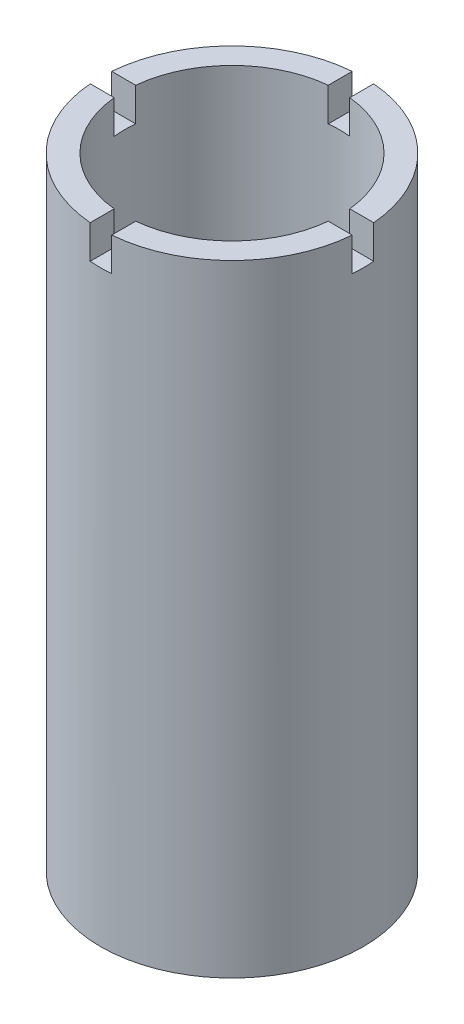
SolidWorks part; units mm, degrees
ref_plane "Front Plane" through (0, 0, 0) normal (0, 0, 1) x (1, 0, 0)
ref_plane "Top Plane" through (0, 0, 0) normal (0, 1, 0) x (1, 0, 0)
ref_plane "Right Plane" through (0, 0, 0) normal (1, 0, 0) x (0, 0, -1)
sketch "Sketch1" plane through (0, 0, 0) normal (0, 1, 0) x (1, 0, 0)
  circle A0 centre (0, 0) radius 27.5
  circle A1 centre (0, 0) radius 22.5
  dimension "D1" = 55
  dimension "D2" = 45
extrude "Boss-Extrude1" add sketch "Sketch1" along normal blind 130
sketch "Sketch2" plane through (0, 130, 0) normal (0, 1, 0) x (1, 0, 0)
  line L1 (-27.4078, 2.25) -> (-22.3872, 2.25)
  line L3 (-27.4078, -2.25) -> (-22.3872, -2.25)
  line L5 (-27.4372, 1.8579) -> (-22.4192, -1.9057) construction
  line L6 (-27.4372, -1.8579) -> (-22.4192, 1.9057) construction
  line L7 (27.4078, -2.25) -> (22.3872, -2.25)
  line L8 (27.4078, 2.25) -> (22.3872, 2.25)
  line L11 (-2.25, 27.4078) -> (-2.25, 22.3872)
  line L13 (2.25, 27.4078) -> (2.25, 22.3872)
  line L14 (-1.7354, 27.4452) -> (1.6791, 22.4373) construction
  line L15 (-1.6791, 22.4373) -> (1.7354, 27.4452) construction
  line L16 (-2.25, -27.4078) -> (-2.25, -22.3872)
  line L17 (2.25, -27.4078) -> (2.25, -22.3872)
  circle A0 centre (0, 0) radius 22.5 construction
  arc A1 (-22.3872, 2.25) -> (-22.3872, -2.25) centre (0, 0) ccw
  circle A2 centre (0, 0) radius 27.5 construction
  arc A3 (-27.4078, 2.25) -> (-27.4078, -2.25) centre (0, 0) ccw
  arc A4 (-2.25, -22.3872) -> (2.25, -22.3872) centre (0, 0) ccw
  arc A5 (-2.25, -27.4078) -> (2.25, -27.4078) centre (0, 0) ccw
  arc A6 (22.3872, -2.25) -> (22.3872, 2.25) centre (0, 0) ccw
  arc A7 (27.4078, -2.25) -> (27.4078, 2.25) centre (0, 0) ccw
  arc A8 (2.25, 27.4078) -> (-2.25, 27.4078) centre (0, 0) ccw
  arc A9 (2.25, 22.3872) -> (-2.25, 22.3872) centre (0, 0) ccw
  point P4 (-24.96, 0)
  point P11 (0, 0)
  point P17 (0, 24.8999)
  point P23 (0, 0)
extrude "Cut-Extrude1" cut sketch "Sketch2" against normal blind 7
